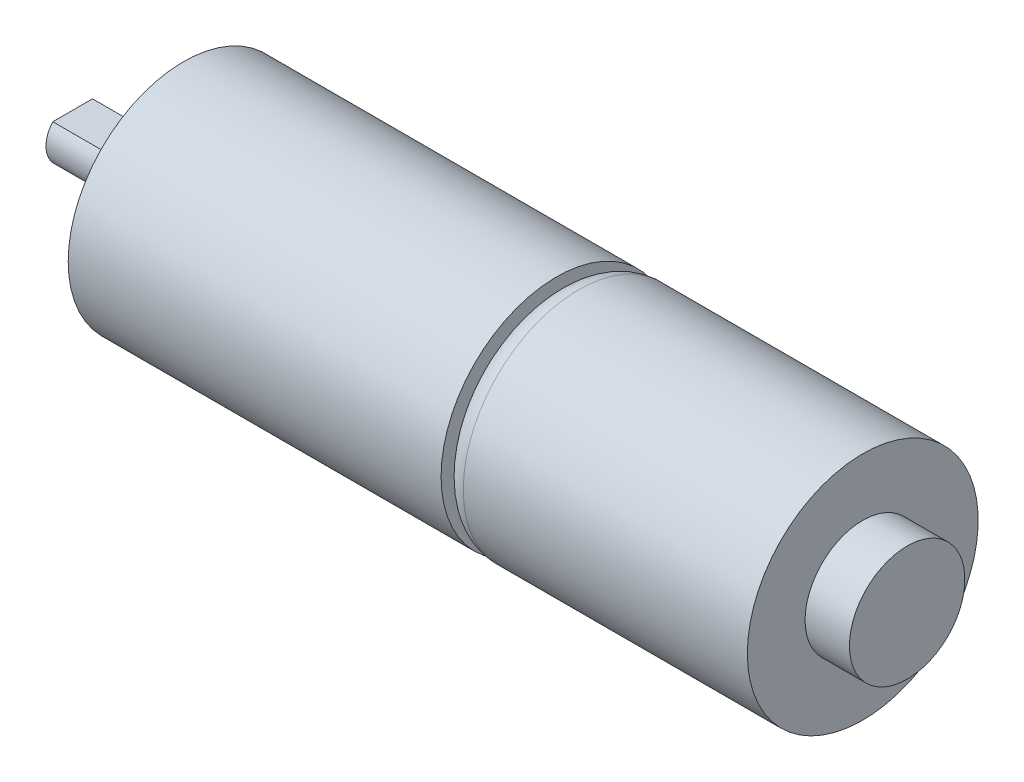
SolidWorks part; units mm, degrees
ref_plane "前基準面" through (0, 0, 0) normal (0, 0, 1) x (1, 0, 0)
ref_plane "上基準面" through (0, 0, 0) normal (0, 1, 0) x (1, 0, 0)
ref_plane "右基準面" through (0, 0, 0) normal (1, 0, 0) x (0, 0, -1)
sketch "草圖1" plane through (0, 0, 0) normal (0, 0, 1) x (1, 0, 0)
  line L0 (-79, 26) -> (-74, 26) construction
  line L1 (-188, 0) -> (-188, 6)
  line L2 (-188, 6) -> (-166, 6)
  line L3 (-163, 16) -> (-163, 26)
  line L4 (-163, 26) -> (-79, 26)
  line L5 (-79, 26) -> (-79, 21)
  line L6 (-74, 26) -> (-10, 26)
  line L7 (-10, 26) -> (-10, 13)
  line L8 (-163, 16) -> (-166, 16)
  line L9 (-166, 16) -> (-166, 6)
  line L10 (-10, 13) -> (0, 13)
  line L11 (0, 13) -> (0, 0)
  line L12 (-188, 0) -> (0, 0)
  arc A0 (-79, 21) -> (-74, 26) centre (-74, 21) cw
  dimension "D9" = 5
  dimension "D1" = 26
  dimension "D2" = 69
  dimension "D3" = 84
  dimension "D4" = 3
  dimension "D5" = 22
  dimension "D6" = 6
  dimension "D7" = 16
  dimension "D8" = 10
  dimension "D10" = 13
revolve "旋轉1" add sketch "草圖1" angle 360 about L12
sketch "草圖2" plane through (0, 0, 0) normal (0, 0, 1) x (1, 0, 0)
  line L1 (-188, 6) -> (-173, 6)
  line L2 (-188, 6) -> (-188, 4)
  line L3 (-188, 4) -> (-173, 4)
  line L4 (-173, 6) -> (-173, 4)
  dimension "D1" = 15
  dimension "D2" = 2
extrude "伸長1" cut sketch "草圖2" against normal through all and the other way through all
sketch "草圖3" plane through (-166, 0, 0) normal (-1, 0, 0) x (0, 0, 1)
  line L0 (0, 0) -> (0, 26) construction
  line L1 (0, 0) -> (26, 0) construction
  line L2 (0, 0) -> (-26, 0) construction
  line L3 (0, 0) -> (0, -26) construction
  circle A0 centre (0, 0) radius 20 construction
  circle A1 centre (0, 0) radius 26 construction
  circle A2 centre (0, 20) radius 2.25
  circle A3 centre (20, 0) radius 2.25
  circle A4 centre (0, -20) radius 2.25
  circle A5 centre (-20, 0) radius 2.25
  dimension "D1" = 40
  dimension "D2" = 4.5
extrude "伸長2" cut sketch "草圖3" against normal blind 10
